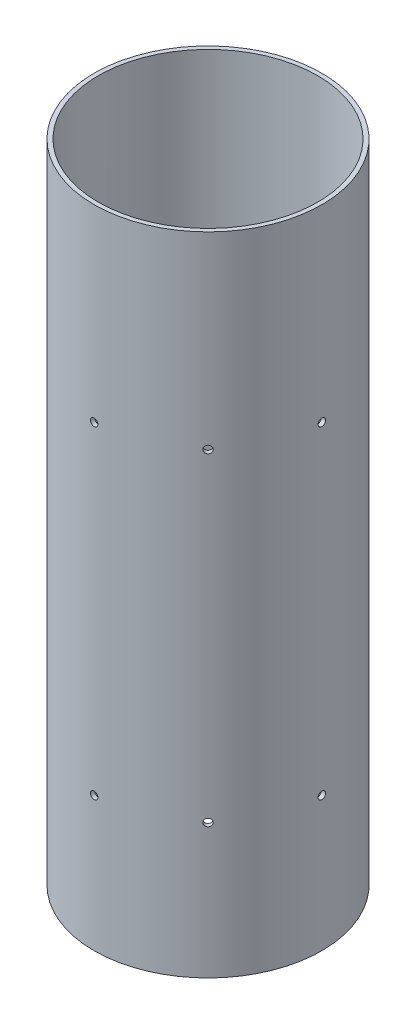
SolidWorks part; units mm, degrees
material "E-Glass Fiber"
ref_plane "Front Plane" through (0, 0, 0) normal (0, 0, 1) x (1, 0, 0)
ref_plane "Top Plane" through (0, 0, 0) normal (0, 1, 0) x (1, 0, 0)
ref_plane "Right Plane" through (0, 0, 0) normal (1, 0, 0) x (0, 0, -1)
sketch "Sketch1" plane through (0, 0, 0) normal (0, 1, 0) x (1, 0, 0)
  circle A0 centre (0, 0) radius 53.721
  circle A1 centre (0, 0) radius 51.7271
  dimension "D1" = 107.442
  dimension "D2" = 103.4542
extrude "Boss-Extrude1" add sketch "Sketch1" along normal blind 304.8
sketch "Sketch2" plane through (0, 0, 0) normal (0, 0, 1) x (1, 0, 0)
  line L2 (0, 0) -> (0, 63.5)
  circle A0 centre (0, 63.5) radius 1.7526
  point P7 (0, 0)
  dimension "D2" = 3.5052
  dimension "D1" = 63.5
extrude "Cut-Extrude2" cut sketch "Sketch2" against normal blind 127 contours A0
pattern_circular "CirPattern1" count 8 over 360 about axis through (0, 304.8, 0) along (0, -1, 0) of "Cut-Extrude2"
sketch "Sketch3" plane through (0, 0, 0) normal (0, 0, 1) x (1, 0, 0)
  line L0 (0, 304.8) -> (0, 0) construction
  line L1 (51.7271, 304.8) -> (-51.7271, 304.8) construction
  line L2 (-53.721, 0) -> (53.721, 0) construction
  circle A1 centre (0, 215.9) radius 1.7526
  dimension "D1" = 3.5052
  dimension "D2" = 88.9
extrude "Cut-Extrude3" cut sketch "Sketch3" against normal blind 127 contours A1
pattern_circular "CirPattern2" count 8 over 360 about axis through (0, 304.8, 0) along (0, -1, 0) of "Cut-Extrude3"
